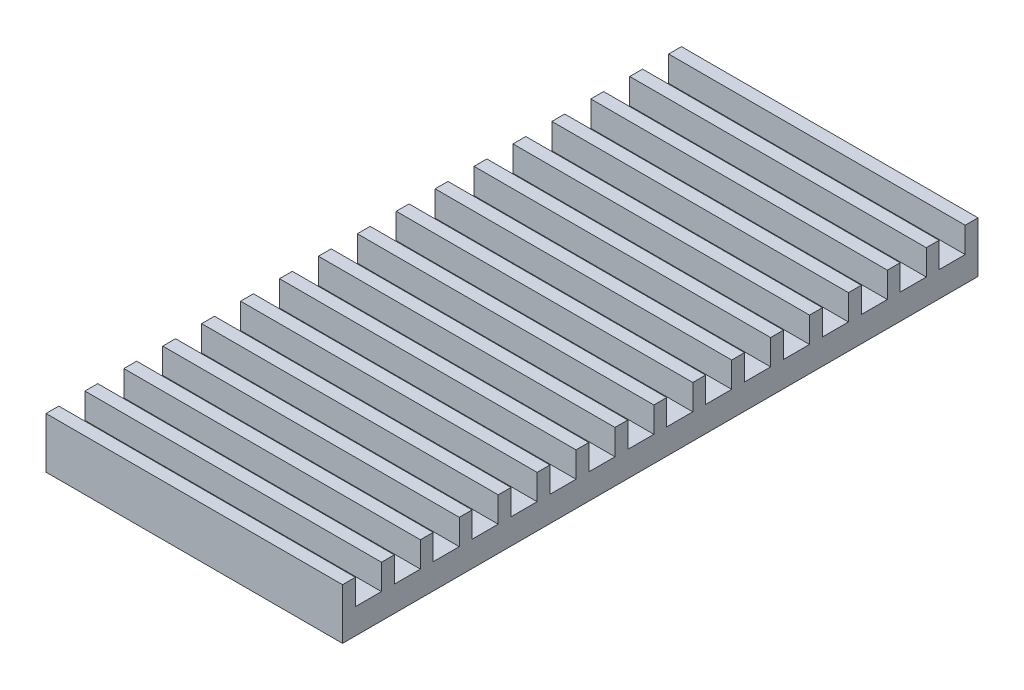
SolidWorks part; units mm, degrees
ref_plane "Front Plane" through (0, 0, 0) normal (0, 0, 1) x (1, 0, 0)
ref_plane "Top Plane" through (0, 0, 0) normal (0, 1, 0) x (1, 0, 0)
ref_plane "Right Plane" through (0, 0, 0) normal (1, 0, 0) x (0, 0, -1)
sketch "Sketch1" plane through (0, 0, 0) normal (0, 1, 0) x (1, 0, 0)
  line L1 (0, 0) -> (70, 0)
  line L2 (0, 0) -> (0, 150)
  line L3 (0, 150) -> (70, 150)
  line L4 (70, 0) -> (70, 150)
  dimension "D1" = 70
  dimension "D2" = 150
extrude "Boss-Extrude1" add sketch "Sketch1" along normal blind 6
sketch "Sketch2" plane through (0, 6, 0) normal (0, 1, 0) x (1, 0, 0)
  line L0 (70, 0) -> (70, 150) construction
  line L1 (0, 0) -> (70, 0)
  line L2 (0, 0) -> (0, 3.0237)
  line L3 (0, 3.0237) -> (70, 3.0237)
  line L4 (70, 0) -> (70, 3.0237)
  line L5 (0, 9.186) -> (0, 12.2097)
  line L6 (0, 9.186) -> (70, 9.186)
  line L7 (70, 9.186) -> (70, 12.2097)
  line L8 (0, 12.2097) -> (70, 12.2097)
  line L9 (0, 18.372) -> (0, 21.3958)
  line L10 (0, 18.372) -> (70, 18.372)
  line L11 (70, 18.372) -> (70, 21.3958)
  line L12 (0, 21.3958) -> (70, 21.3958)
  line L13 (0, 27.5581) -> (0, 30.5818)
  line L14 (0, 27.5581) -> (70, 27.5581)
  line L15 (70, 27.5581) -> (70, 30.5818)
  line L16 (0, 30.5818) -> (70, 30.5818)
  line L17 (0, 36.7441) -> (0, 39.7678)
  line L18 (0, 36.7441) -> (70, 36.7441)
  line L19 (70, 36.7441) -> (70, 39.7678)
  line L20 (0, 39.7678) -> (70, 39.7678)
  line L21 (0, 45.9301) -> (0, 48.9538)
  line L22 (0, 45.9301) -> (70, 45.9301)
  line L23 (70, 45.9301) -> (70, 48.9538)
  line L24 (0, 48.9538) -> (70, 48.9538)
  line L25 (0, 55.1161) -> (0, 58.1398)
  line L26 (0, 55.1161) -> (70, 55.1161)
  line L27 (70, 55.1161) -> (70, 58.1398)
  line L28 (0, 58.1398) -> (70, 58.1398)
  line L29 (0, 64.3021) -> (0, 67.3258)
  line L30 (0, 64.3021) -> (70, 64.3021)
  line L31 (70, 64.3021) -> (70, 67.3258)
  line L32 (0, 67.3258) -> (70, 67.3258)
  line L33 (0, 73.4881) -> (0, 76.5119)
  line L34 (0, 73.4881) -> (70, 73.4881)
  line L35 (70, 73.4881) -> (70, 76.5119)
  line L36 (0, 76.5119) -> (70, 76.5119)
  line L37 (0, 82.6742) -> (0, 85.6979)
  line L38 (0, 82.6742) -> (70, 82.6742)
  line L39 (70, 82.6742) -> (70, 85.6979)
  line L40 (0, 85.6979) -> (70, 85.6979)
  line L41 (0, 91.8602) -> (0, 94.8839)
  line L42 (0, 91.8602) -> (70, 91.8602)
  line L43 (70, 91.8602) -> (70, 94.8839)
  line L44 (0, 94.8839) -> (70, 94.8839)
  line L45 (0, 101.0462) -> (0, 104.0699)
  line L46 (0, 101.0462) -> (70, 101.0462)
  line L47 (70, 101.0462) -> (70, 104.0699)
  line L48 (0, 104.0699) -> (70, 104.0699)
  line L49 (0, 110.2322) -> (0, 113.2559)
  line L50 (0, 110.2322) -> (70, 110.2322)
  line L51 (70, 110.2322) -> (70, 113.2559)
  line L52 (0, 113.2559) -> (70, 113.2559)
  line L53 (0, 119.4182) -> (0, 122.4419)
  line L54 (0, 119.4182) -> (70, 119.4182)
  line L55 (70, 119.4182) -> (70, 122.4419)
  line L56 (0, 122.4419) -> (70, 122.4419)
  line L57 (0, 128.6042) -> (0, 131.628)
  line L58 (0, 128.6042) -> (70, 128.6042)
  line L59 (70, 128.6042) -> (70, 131.628)
  line L60 (0, 131.628) -> (70, 131.628)
  line L61 (0, 137.7903) -> (0, 140.814)
  line L62 (0, 137.7903) -> (70, 137.7903)
  line L63 (70, 137.7903) -> (70, 140.814)
  line L64 (0, 140.814) -> (70, 140.814)
  line L65 (0, 146.9763) -> (0, 150)
  line L66 (0, 146.9763) -> (70, 146.9763)
  line L67 (70, 146.9763) -> (70, 150)
  line L68 (0, 150) -> (70, 150)
  line L70 (70, 150) -> (0, 150) construction
  dimension "D1" = 17
extrude "Boss-Extrude2" add sketch "Sketch2" along normal blind 6
